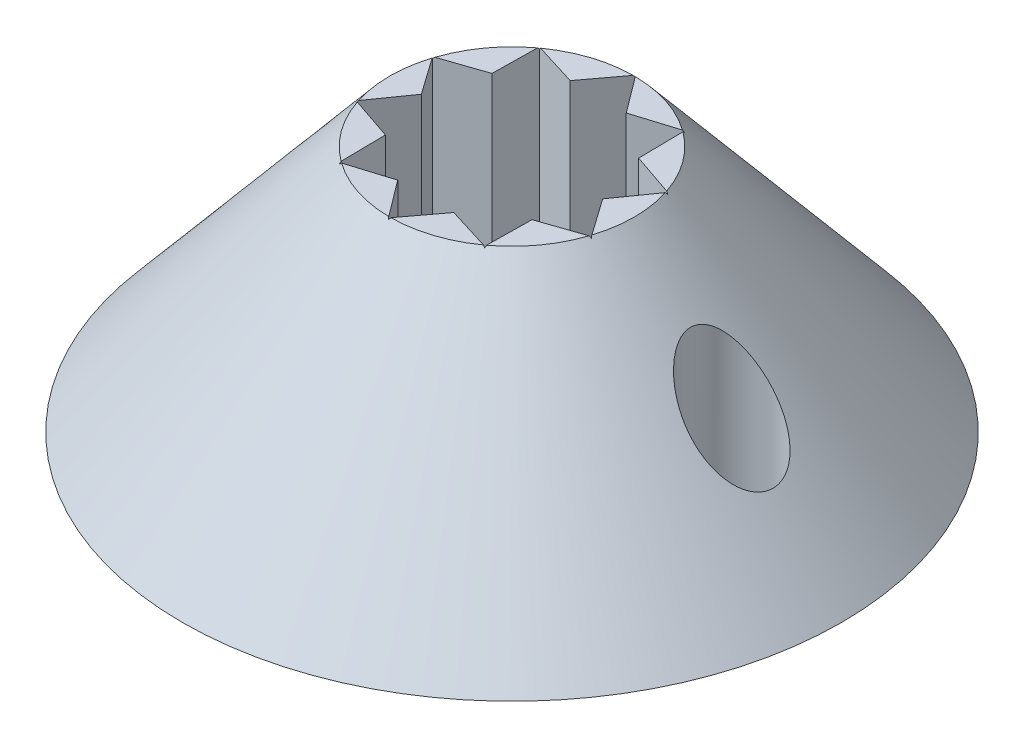
SolidWorks part; units mm, degrees
ref_plane "Спереди" through (0, 0, 0) normal (0, 0, 1) x (1, 0, 0)
ref_plane "Сверху" through (0, 0, 0) normal (0, 1, 0) x (1, 0, 0)
ref_plane "Справа" through (0, 0, 0) normal (1, 0, 0) x (0, 0, -1)
sketch "Sketch1" plane through (0, 0, 0) normal (0, 1, 0) x (1, 0, 0)
  circle A0 centre (0, 0) radius 6
  dimension "D1" = 12
extrude "Boss-Extrude1" add sketch "Sketch1" along normal blind 4.5 draft 40
sketch "Sketch3" plane through (0, 4.5, 0) normal (0, 1, 0) x (1, 0, 0)
  line L0 (0, 0) -> (0, 2.25) construction
  line L1 (0, 2.25) -> (-0.5099, 1.5692)
  line L2 (0, 2.25) -> (0.5099, 1.5692)
  line L3 (1.3225, 1.8203) -> (1.3349, 0.9698)
  line L4 (1.3225, 1.8203) -> (0.5099, 1.5692)
  line L5 (2.1399, 0.6953) -> (1.65, 0)
  line L6 (2.1399, 0.6953) -> (1.3349, 0.9698)
  line L7 (2.1399, -0.6953) -> (1.3349, -0.9698)
  line L8 (2.1399, -0.6953) -> (1.65, 0)
  line L9 (1.3225, -1.8203) -> (0.5099, -1.5692)
  line L10 (1.3225, -1.8203) -> (1.3349, -0.9698)
  line L11 (0, -2.25) -> (-0.5099, -1.5692)
  line L12 (0, -2.25) -> (0.5099, -1.5692)
  line L13 (-1.3225, -1.8203) -> (-1.3349, -0.9698)
  line L14 (-1.3225, -1.8203) -> (-0.5099, -1.5692)
  line L15 (-2.1399, -0.6953) -> (-1.65, 0)
  line L16 (-2.1399, -0.6953) -> (-1.3349, -0.9698)
  line L17 (-2.1399, 0.6953) -> (-1.3349, 0.9698)
  line L18 (-2.1399, 0.6953) -> (-1.65, 0)
  line L19 (-1.3225, 1.8203) -> (-0.5099, 1.5692)
  line L20 (-1.3225, 1.8203) -> (-1.3349, 0.9698)
  circle A0 centre (0, 0) radius 1.65 construction
  circle A1 centre (0, 0) radius 2.25 construction
  point P23 (0, 0)
  dimension "D1" = 4.5
  dimension "D2" = 3.3
extrude "Cut-Extrude1" cut sketch "Sketch3" against normal blind 5
sketch "Sketch5" plane through (0, 0, 0) normal (0, -1, 0) x (1, 0, 0)
  line L0 (-4, 0) -> (4, 0) construction
  circle A0 centre (4, 0) radius 0.75
  circle A1 centre (-4, 0) radius 0.75
  point P4 (0, 0)
  dimension "D1" = 1.5
  dimension "D2" = 8
extrude "Cut-Extrude2" cut sketch "Sketch5" against normal blind 5
